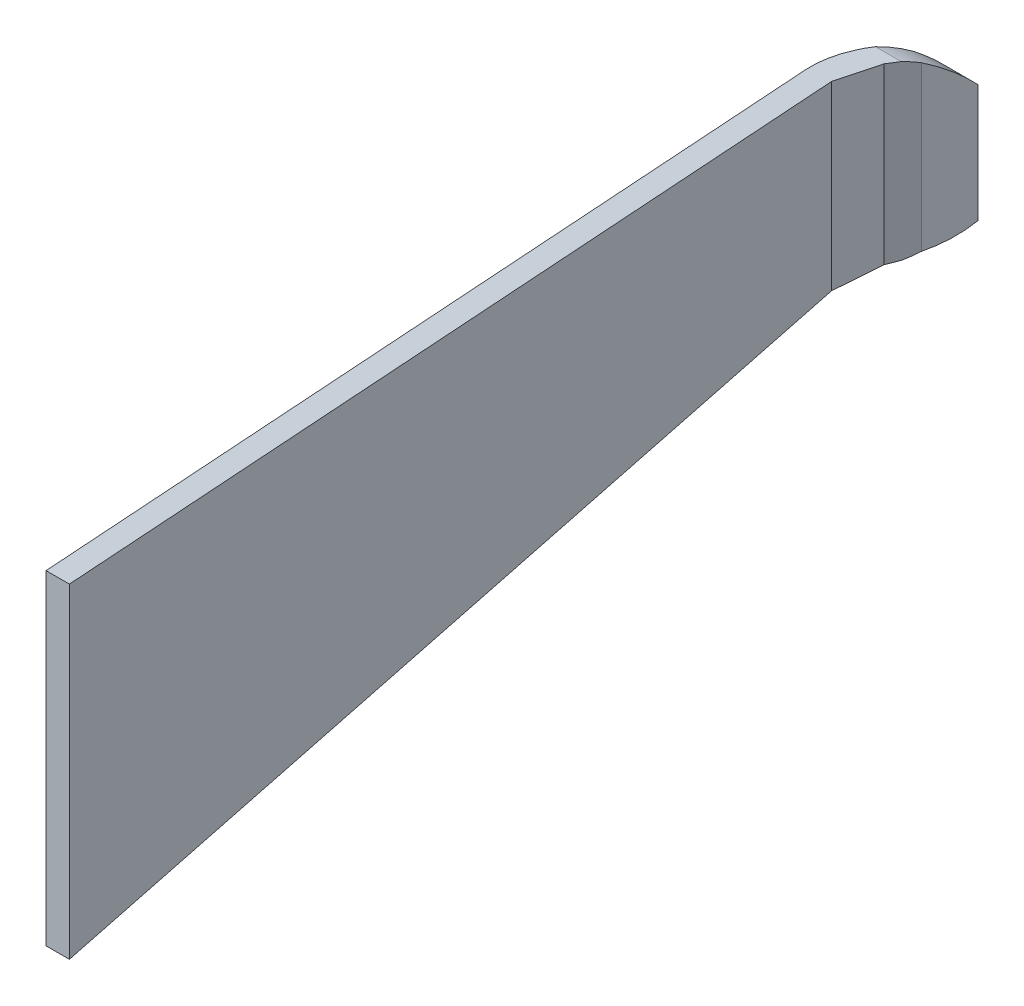
SolidWorks part; units mm, degrees
ref_plane "Front Plane" through (0, 0, 0) normal (0, 0, 1) x (1, 0, 0)
ref_plane "Top Plane" through (0, 0, 0) normal (0, 1, 0) x (1, 0, 0)
ref_plane "Right Plane" through (0, 0, 0) normal (1, 0, 0) x (0, 0, -1)
sketch "Sketch2" plane through (0, 0, 0) normal (0, 1, 0) x (1, 0, 0)
  line L0 (7.3508, -4.074) -> (6.5259, 1.6935)
  line L1 (6.5729, 1.9863) -> (6.6534, 2.1487)
  line L2 (6.6534, 2.1487) -> (6.8122, 2.3569)
  line L3 (6.5259, 1.6935) -> (6.5729, 1.9863)
  line L4 (7.3508, -4.074) -> (7.2008, -4.074)
  line L5 (7.1993, -4.074) -> (6.3774, 1.6722)
  line L6 (6.4385, 2.053) -> (6.5254, 2.2283)
  line L7 (6.5254, 2.2283) -> (6.693, 2.4479)
  line L8 (7.2023, -4.0953) -> (6.3774, 1.6722) construction
  line L9 (7.2008, -4.074) -> (7.1993, -4.074)
  line L10 (6.693, 2.4479) -> (6.8122, 2.3569)
  arc A0 (6.3774, 1.6722) -> (6.4385, 2.053) centre (7.0209, 1.7643) cw
  arc A2 (6.5259, 1.6935) -> (6.5729, 1.9863) centre (7.0209, 1.7643) cw construction
  dimension "D2" = 0.15
extrude "Boss-Extrude1" add sketch "Sketch2" along normal blind 3
sketch "Sketch3" plane through (6.6325, 0, -0.9486) normal (0.9899, 0, -0.1416) x (-0.1416, 0, -0.9899)
  line L0 (-5.265, 2.9135) -> (-5.265, 3.467)
  line L1 (-5.265, 3.467) -> (2.2373, 3.467)
  line L2 (2.2373, 3.467) -> (2.2373, -0.4097)
  line L3 (2.2373, -0.4097) -> (-5.2757, -0.4097)
  line L4 (-5.2757, -0.4097) -> (-5.2649, 0.1368)
  line L35 (-5.4057, 2.7438) -> (-5.4057, 2.7839)
  line L36 (-5.4057, 0.2663) -> (-5.4057, 0.3064)
  line L38 (-5.1057, 0.4511) -> (-5.2865, 0.436)
  line L39 (-4.8554, 2.5789) -> (1.1342, 2.0874)
  line L40 (-4.8554, 2.5789) -> (-5.1057, 2.5994)
  line L42 (1.1348, 0.9708) -> (-4.8554, 0.4719)
  line L43 (-5.1057, 0.4511) -> (-4.8554, 0.4719)
  line L45 (-5.1057, 2.5994) -> (-5.2863, 2.6142)
  arc A20 (-5.2863, 2.6142) -> (-5.4057, 2.7438) centre (-5.2757, 2.7438) cw
  arc A21 (-5.4057, 2.7839) -> (-5.265, 2.9135) centre (-5.2757, 2.7839) cw
  arc A22 (-5.2865, 0.436) -> (-5.4057, 0.3064) centre (-5.2757, 0.3064) ccw
  arc A24 (-5.2649, 0.1368) -> (-5.4057, 0.2663) centre (-5.2757, 0.2663) cw
  arc A28 (1.1342, 2.0874) -> (1.1348, 0.9708) centre (0.9656, 1.529) cw
  point P0 (-5.6656, -9.3154)
  point P1 (-5.3656, -9.6414)
  point P2 (-5.6656, -12.1154)
  point P3 (1.3334, -10.1994)
  point P24 (1.3334, -11.2401)
  point P25 (-5.3656, -11.7898)
  point P114 (-5.4057, 2.624)
sketch "Sketch5" plane through (0, 3, 0) normal (0, 1, 0) x (1, 0, 0)
  line L0 (7.3508, -4.074) -> (7.3508, -4.075)
  line L1 (7.3508, -4.075) -> (7.1993, -4.075)
  line L2 (7.1993, -4.075) -> (7.1993, -4.074)
  line L3 (7.1993, -4.074) -> (7.3508, -4.074)
extrude "Boss-Extrude2" add sketch "Sketch5" against normal up to vertex (3 mm away)
sketch "Sketch6" plane through (7.3508, 0, 0) normal (1, 0, 0) x (0, 0, -1)
  line L0 (-4.3382, 2.8846) -> (-4.3382, 3.4382)
  line L1 (-4.3382, 3.4382) -> (3.1641, 3.4382)
  line L2 (3.1641, 3.4382) -> (3.1641, -0.4385)
  line L3 (3.1641, -0.4385) -> (-4.3488, -0.4385)
  line L4 (-4.3488, -0.4385) -> (-4.3376, 0.1325)
  line L5 (-4.3596, 0.4317) -> (2.0617, 0.9419)
  line L6 (-4.075, 0.455) -> (-4.5059, 0.4197) construction
  line L35 (-4.4788, 2.7149) -> (-4.4788, 2.7551)
  line L36 (-4.4788, 0.262) -> (-4.4788, 0.3021)
  line L39 (-3.9286, 2.55) -> (2.061, 2.0585)
  line L40 (-3.9286, 2.55) -> (-4.1788, 2.5705)
  line L45 (-4.1788, 2.5705) -> (-4.3595, 2.5854)
  arc A0 (-4.3596, 0.4317) -> (-4.4788, 0.3021) centre (-4.3545, 0.3073) ccw
  arc A1 (2.061, 2.0585) -> (2.0617, 0.9419) centre (1.9286, 1.5002) cw
  arc A20 (-4.3595, 2.5854) -> (-4.4788, 2.7149) centre (-4.3488, 2.7149) cw
  arc A21 (-4.4788, 2.7551) -> (-4.3382, 2.8846) centre (-4.3488, 2.7551) cw
  arc A24 (-4.3376, 0.1325) -> (-4.4788, 0.262) centre (-4.3488, 0.262) cw
  point P0 (-8.1817, -8.6207)
  point P1 (-7.8817, -8.9467)
  point P2 (-8.1817, -11.4207)
  point P3 (-1.1826, -9.5046)
  point P24 (-1.1827, -10.5454)
  point P25 (-7.8817, -11.095)
  point P114 (-4.4788, 2.5951)
extrude "Cut-Extrude1" cut sketch "Sketch6" against normal blind 10
